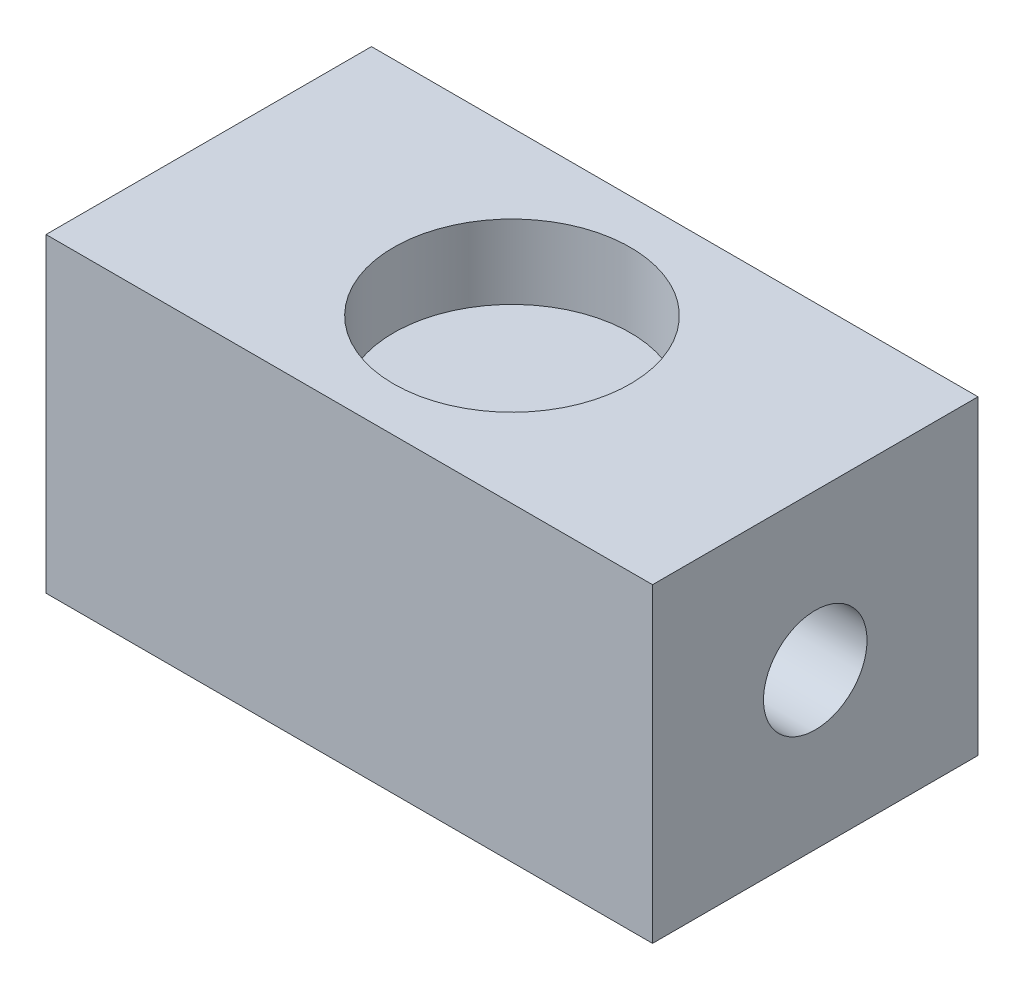
SolidWorks part; units mm, degrees
ref_plane "Front Plane" through (0, 0, 0) normal (0, 0, 1) x (1, 0, 0)
ref_plane "Top Plane" through (0, 0, 0) normal (0, 1, 0) x (1, 0, 0)
ref_plane "Right Plane" through (0, 0, 0) normal (1, 0, 0) x (0, 0, -1)
sketch "Sketch1" plane through (0, 0, 0) normal (1, 0, 0) x (0, 0, -1)
  line L1 (27.94, -26.67) -> (-27.94, -26.67)
  line L2 (27.94, -26.67) -> (27.94, 26.67)
  line L3 (27.94, 26.67) -> (-27.94, 26.67)
  line L4 (-27.94, -26.67) -> (-27.94, 26.67)
  line L5 (27.94, -26.67) -> (-27.94, 26.67) construction
  line L6 (27.94, 26.67) -> (-27.94, -26.67) construction
  point P0 (0, 0)
extrude "Boss-Extrude1" add sketch "Sketch1" along normal blind 104.14
sketch "Sketch2" plane through (104.14, 0, 0) normal (1, 0, 0) x (0, 0, -1)
  circle A0 centre (0, 0) radius 8.89
extrude "Cut-Extrude1" cut sketch "Sketch2" against normal through all
sketch "Sketch3" plane through (0, 26.67, 0) normal (0, 1, 0) x (1, 0, 0)
  circle A0 centre (52.07, 0) radius 20.32
extrude "Cut-Extrude2" cut sketch "Sketch3" against normal blind 12.7
